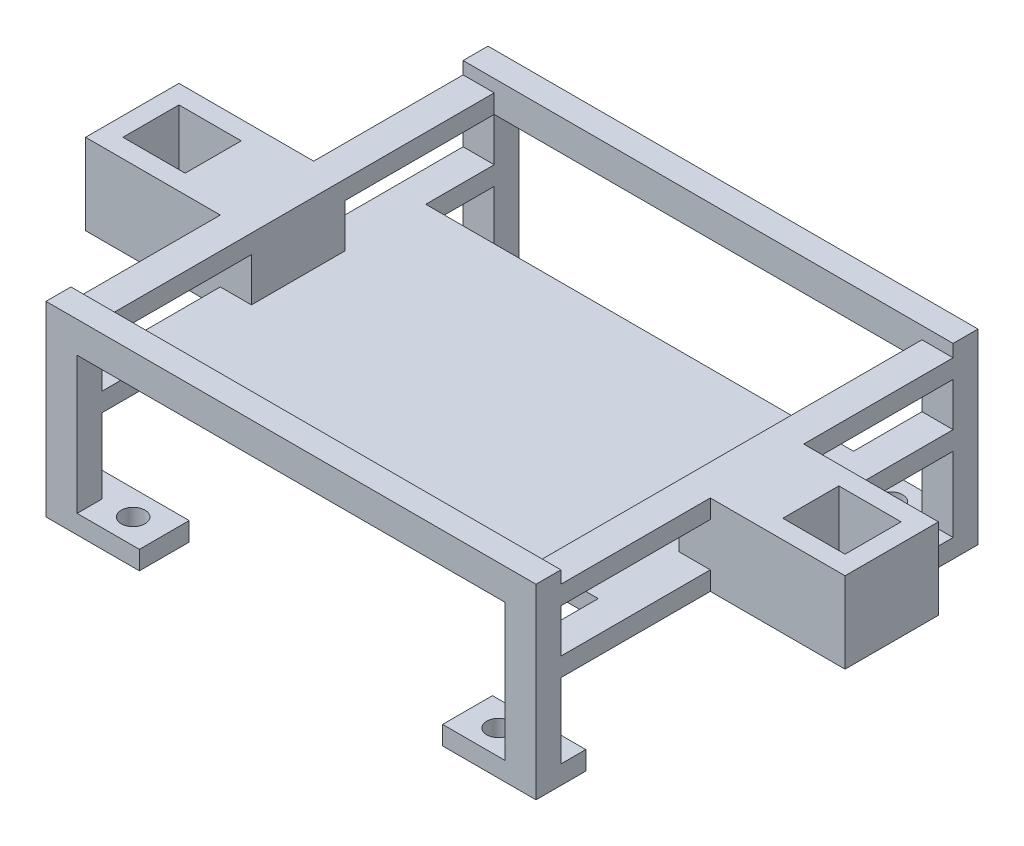
SolidWorks part; units mm, degrees
ref_plane "Front Plane" through (0, 0, 0) normal (0, 0, 1) x (1, 0, 0)
ref_plane "Top Plane" through (0, 0, 0) normal (0, 1, 0) x (1, 0, 0)
ref_plane "Right Plane" through (0, 0, 0) normal (1, 0, 0) x (0, 0, -1)
sketch "Sketch1" plane through (0, 0, 0) normal (0, 1, 0) x (1, 0, 0)
  line L0 (0, 0) -> (-34.355, 0) construction
  line L1 (-39.355, 31.5) -> (-34.355, 31.5)
  line L2 (-39.355, 31.5) -> (-39.355, -31.5)
  line L3 (-39.355, -31.5) -> (-34.355, -31.5)
  line L4 (-34.355, 31.5) -> (-34.355, -31.5)
  line L5 (0, 0) -> (0, 31.4679) construction
  line L6 (34.355, 31.5) -> (34.355, -31.5)
  line L7 (39.355, -31.5) -> (34.355, -31.5)
  line L8 (39.355, 31.5) -> (39.355, -31.5)
  line L9 (39.355, 31.5) -> (34.355, 31.5)
  dimension "D1" = 63
  dimension "D2" = 5
  dimension "D3" = 68.71
extrude "Boss-Extrude1" add sketch "Sketch1" along normal blind 3
sketch "Sketch2" plane through (0, 3, 0) normal (0, 1, 0) x (1, 0, 0)
  line L0 (-34.355, 0) -> (-39.355, 0) construction
  line L1 (-34.355, -31.5) -> (-34.355, 31.5) construction
  line L2 (-39.355, 31.5) -> (-39.355, -31.5) construction
  line L3 (34.355, 0) -> (39.355, 0) construction
  line L4 (34.355, 31.5) -> (34.355, -31.5) construction
  line L5 (39.355, -31.5) -> (39.355, 31.5) construction
  circle A0 centre (36.855, 0) radius 1.395
  circle A1 centre (-36.855, 0) radius 1.395
  dimension "D1" = 2.79
extrude "pegs" [suppressed] add sketch "Sketch2" along normal blind 6.35
sketch "Sketch3" plane through (0, 0, 31.5) normal (0, 0, 1) x (1, 0, 0)
  line L0 (39.355, 3) -> (39.355, 0) construction
  line L1 (-39.355, 0) -> (39.355, 0)
  line L2 (-39.355, 0) -> (-39.355, 5)
  line L3 (-39.355, 5) -> (39.355, 5)
  line L4 (39.355, 0) -> (39.355, 5)
  dimension "D1" = 5
extrude "Boss-Extrude3" add sketch "Sketch3" along normal blind 4
sketch "Sketch4" plane through (0, 0, -31.5) normal (0, 0, -1) x (-1, 0, 0)
  line L4 (39.355, 0) -> (39.355, 5)
  line L5 (-39.355, 0) -> (39.355, 0)
  line L6 (-39.355, 5) -> (-39.355, 0)
  line L7 (39.355, 5) -> (-39.355, 5)
  line L8 (39.355, 0) -> (39.355, 5)
  line L9 (-39.355, 0) -> (39.355, 0)
  line L10 (-39.355, 5) -> (-39.355, 0)
  line L11 (39.355, 5) -> (-39.355, 5)
  dimension "D1" = 0
extrude "Boss-Extrude4" add sketch "Sketch4" along normal blind 4
ref_plane "mirror plane" through (0, 0, 0) normal (-1, 0, 0) x (0, 0, 1)
sketch "Sketch5" plane through (0, 0, 0) normal (0, -1, 0) x (1, 0, 0)
  line L0 (-39.355, 35.5) -> (39.355, 35.5) construction
  line L1 (-39.355, 35.5) -> (-34.355, 35.5)
  line L2 (-39.355, 35.5) -> (-39.355, 31.5)
  line L3 (-39.355, 31.5) -> (-34.355, 31.5)
  line L4 (-34.355, 35.5) -> (-34.355, 31.5)
  line L5 (-34.355, 31.5) -> (34.355, 31.5) construction
  line L6 (0, 0) -> (-19.4974, 0) construction
  line L7 (34.355, 35.5) -> (39.355, 35.5)
  line L8 (34.355, 35.5) -> (34.355, 31.5)
  line L9 (34.355, 31.5) -> (39.355, 31.5)
  line L10 (39.355, 35.5) -> (39.355, 31.5)
  line L11 (-34.355, -35.5) -> (-34.355, -31.5)
  line L12 (-39.355, -31.5) -> (-34.355, -31.5)
  line L13 (-39.355, -35.5) -> (-39.355, -31.5)
  line L14 (-39.355, -35.5) -> (-34.355, -35.5)
  line L15 (39.355, -35.5) -> (39.355, -31.5)
  line L16 (34.355, -31.5) -> (39.355, -31.5)
  line L17 (34.355, -35.5) -> (34.355, -31.5)
  line L18 (34.355, -35.5) -> (39.355, -35.5)
  line L19 (-39.355, -35.5) -> (-39.355, 35.5) construction
  line L22 (39.355, 35.5) -> (39.355, -35.5) construction
  dimension "D1" = 5
sketch "Sketch6" plane through (-39.355, 0, 0) normal (-1, 0, 0) x (0, 0, 1)
  line L0 (0, 0) -> (0, 3) construction
  line L1 (-35.5, 0) -> (35.5, 0) construction
  line L2 (-31.5, 3) -> (31.5, 3) construction
  line L4 (-7.5, 0) -> (7.5, 0)
  line L5 (-7.5, 0) -> (-7.5, 3)
  line L6 (-7.5, 3) -> (7.5, 3)
  line L7 (7.5, 0) -> (7.5, 3)
  line L8 (-7.5, 0) -> (7.5, 3) construction
  line L9 (-7.5, 3) -> (7.5, 0) construction
  point P6 (0, 1.5)
  dimension "D1" = 15
extrude "Boss-Extrude5" add sketch "Sketch6" along normal offset from surface (5.645 mm away) 45 up to plane "mirror plane"
sketch "Sketch7" plane through (0, 3, 0) normal (0, 1, 0) x (1, 0, 0)
  line L0 (-45, 0) -> (-61, 0) construction
  line L1 (-45, -7.5) -> (-45, 7.5) construction
  line L2 (-61, 7.5) -> (-45, 7.5)
  line L3 (-58, -4.5) -> (-48, -4.5)
  line L4 (-58, -4.5) -> (-58, 4.5)
  line L5 (-58, 4.5) -> (-48, 4.5)
  line L6 (-48, -4.5) -> (-48, 4.5)
  line L7 (-58, -4.5) -> (-48, 4.5) construction
  line L8 (-58, 4.5) -> (-48, -4.5) construction
  line L9 (-45, -7.5) -> (-45, 7.5)
  line L10 (-61, -7.5) -> (-45, -7.5)
  line L11 (-61, -7.5) -> (-61, 7.5)
  point P5 (-53, 0)
  dimension "D1" = 9
  dimension "D2" = 10
  dimension "D3" = 3
extrude "Boss-Extrude6" add sketch "Sketch7" against normal up to surface (3 mm away) up to face at (-21.7944, 0, -3.5)
extrude "legs" add sketch "Sketch5" along normal blind 25
sketch "Sketch12" plane through (0, -25, 0) normal (0, -1, 0) x (1, 0, 0)
  line L0 (0, 0) -> (21.8293, 0) construction
  line L1 (39.355, 35.5) -> (24.355, 35.5)
  line L2 (39.355, 35.5) -> (39.355, 27.5)
  line L3 (39.355, 27.5) -> (24.355, 27.5)
  line L4 (24.355, 35.5) -> (24.355, 27.5)
  line L5 (0, 0) -> (0, 55.0745) construction
  line L6 (24.355, -35.5) -> (24.355, -27.5)
  line L7 (39.355, -27.5) -> (24.355, -27.5)
  line L8 (39.355, -35.5) -> (39.355, -27.5)
  line L9 (39.355, -35.5) -> (24.355, -35.5)
  line L10 (-39.355, -35.5) -> (-24.355, -35.5)
  line L11 (-39.355, -35.5) -> (-39.355, -27.5)
  line L12 (-39.355, -27.5) -> (-24.355, -27.5)
  line L13 (-24.355, -35.5) -> (-24.355, -27.5)
  line L14 (-24.355, 35.5) -> (-24.355, 27.5)
  line L15 (-39.355, 27.5) -> (-24.355, 27.5)
  line L16 (-39.355, 35.5) -> (-39.355, 27.5)
  line L17 (-39.355, 35.5) -> (-24.355, 35.5)
  line L18 (24.355, 31.5) -> (29.355, 31.5) construction
  circle A0 centre (29.355, 31.5) radius 1.905
  circle A1 centre (29.355, -31.5) radius 1.905
  circle A2 centre (-29.355, 31.5) radius 1.905
  circle A3 centre (-29.355, -31.5) radius 1.905
  dimension "D3" = 3.81
  dimension "D1" = 8
  dimension "D2" = 15
  dimension "D4" = 5
extrude "Boss-Extrude10" add sketch "Sketch12" against normal blind 3
sketch "Sketch13" plane through (0, 3, 0) normal (0, 1, 0) x (1, 0, 0)
  line L0 (0, 0) -> (0, 56.786) construction
  line L12 (-58, 4.5) -> (-58, -4.5) construction
  line L13 (-48, -4.5) -> (-48, 4.5) construction
  line L14 (-48, 4.5) -> (-58, 4.5) construction
  line L15 (-61, 7.5) -> (-39.355, 7.5) construction
  line L16 (-48, 4.5) -> (-58, 4.5)
  line L17 (-48, -4.5) -> (-48, 4.5)
  line L18 (-58, -4.5) -> (-48, -4.5)
  line L19 (-58, 4.5) -> (-58, -4.5)
  line L20 (-48, 4.5) -> (-58, 4.5) construction
  line L21 (-48, -4.5) -> (-48, 4.5) construction
  line L22 (-58, -4.5) -> (-48, -4.5) construction
  line L23 (61, -7.5) -> (39.355, -7.5)
  line L24 (61, 7.5) -> (61, -7.5)
  line L25 (61, 7.5) -> (39.355, 7.5)
  line L26 (48, 4.5) -> (58, 4.5)
  line L27 (48, -4.5) -> (48, 4.5)
  line L28 (58, 4.5) -> (58, -4.5)
  line L29 (58, 4.5) -> (58, -4.5)
  line L30 (58, -4.5) -> (48, -4.5)
  line L31 (48, -4.5) -> (48, 4.5)
  line L32 (48, 4.5) -> (58, 4.5)
  line L33 (39.355, 7.5) -> (39.355, -7.5)
  line L35 (-58, 4.5) -> (-58, -4.5) construction
  line L36 (-61, 7.5) -> (-61, -7.5) construction
  line L37 (-61, -7.5) -> (-39.355, -7.5) construction
  line L38 (-58, 4.5) -> (-58, -4.5) construction
  line L39 (-48, -4.5) -> (-48, 4.5) construction
  line L40 (-48, 4.5) -> (-58, 4.5) construction
  line L41 (-61, 7.5) -> (-39.355, 7.5) construction
  line L42 (-61, 7.5) -> (-61, -7.5) construction
  line L43 (-61, -7.5) -> (-39.355, -7.5) construction
  line M4 (39.355, -31.5) -> (39.355, 31.5)
  dimension "D1" = 0
extrude "copy" add sketch "Sketch13" against normal up to surface (3 mm away) contours L24 L25 L23 L28 L30 L27 L26 M4
ref_plane "Plane1" through (0, -10, 0) normal (0, -1, 0) x (-1, 0, 0)
sketch "Sketch14" plane through (0, -10, 0) normal (0, -1, 0) x (-1, 0, 0)
  line L0 (-61, 7.5) -> (-61, -7.5) construction
  line L1 (-39.355, 35.5) -> (-34.355, 35.5)
  line L2 (-39.355, 35.5) -> (-39.355, -35.5)
  line L3 (-39.355, -35.5) -> (-34.355, -35.5)
  line L4 (39.355, 35.5) -> (39.355, -35.5)
  line L6 (-34.355, -35.5) -> (-34.355, -20.5)
  line L7 (-34.355, -20.5) -> (34.355, -20.5)
  line L8 (0, -20.5) -> (0, -35.7583) construction
  line L9 (34.355, -35.5) -> (34.355, -20.5)
  line L10 (34.355, -35.5) -> (39.355, -35.5)
  line L11 (34.355, -31.5) -> (34.355, 31.5) construction
  line L12 (-34.355, 31.5) -> (-34.355, -31.5) construction
  line L13 (-61, 0) -> (61, 0) construction
  line L15 (61, -7.5) -> (61, 7.5) construction
  line L16 (34.355, 35.5) -> (34.355, 20.5)
  line L17 (-34.355, 20.5) -> (34.355, 20.5)
  line L18 (-34.355, 35.5) -> (-34.355, 20.5)
  line L19 (34.355, 35.5) -> (39.355, 35.5)
  dimension "D1" = 15
extrude "Boss-Extrude11" add sketch "Sketch14" against normal blind 3
sketch "Sketch15" plane through (0, 0, 0) normal (0, -1, 0) x (1, 0, 0)
  line L0 (-58, -4.5) -> (-48, -4.5) construction
  line L1 (-58, 4.5) -> (-58, -4.5) construction
  line L2 (-48, 4.5) -> (-58, 4.5) construction
  line L3 (-48, -4.5) -> (-48, 4.5) construction
  line L4 (-61, 7.5) -> (-61, -7.5) construction
  line L5 (-61, -7.5) -> (-39.355, -7.5) construction
  line L6 (-61, 7.5) -> (-39.355, 7.5) construction
  line L7 (-58, -4.5) -> (-48, -4.5)
  line L8 (-58, 4.5) -> (-58, -4.5)
  line L9 (-48, 4.5) -> (-58, 4.5)
  line L10 (-48, -4.5) -> (-48, 4.5)
  line L11 (-61, 7.5) -> (-61, -7.5)
  line L12 (-61, -7.5) -> (-39.355, -7.5)
  line L13 (-61, 7.5) -> (-39.355, 7.5)
  line L14 (-39.355, 7.5) -> (-34.355, 7.5)
  line L15 (-34.355, 31.5) -> (-34.355, -31.5) construction
  line L16 (-39.355, -7.5) -> (-34.355, -7.5)
  line L17 (-34.355, -7.5) -> (-34.355, 7.5)
  line L18 (0, 0) -> (0, -20.5) construction
  line L19 (-34.355, -20.5) -> (34.355, -20.5) construction
  line L20 (34.355, -7.5) -> (34.355, 7.5)
  line L21 (39.355, -7.5) -> (34.355, -7.5)
  line L22 (39.355, 7.5) -> (34.355, 7.5)
  line L23 (61, 7.5) -> (39.355, 7.5)
  line L24 (61, -7.5) -> (39.355, -7.5)
  line L25 (61, 7.5) -> (61, -7.5)
  line L26 (48, -4.5) -> (48, 4.5)
  line L27 (48, 4.5) -> (58, 4.5)
  line L28 (58, 4.5) -> (58, -4.5)
  line L29 (58, -4.5) -> (48, -4.5)
extrude "Boss-Extrude12" add sketch "Sketch15" along normal up to surface (10 mm away) up to face at (0, -10, 0)
